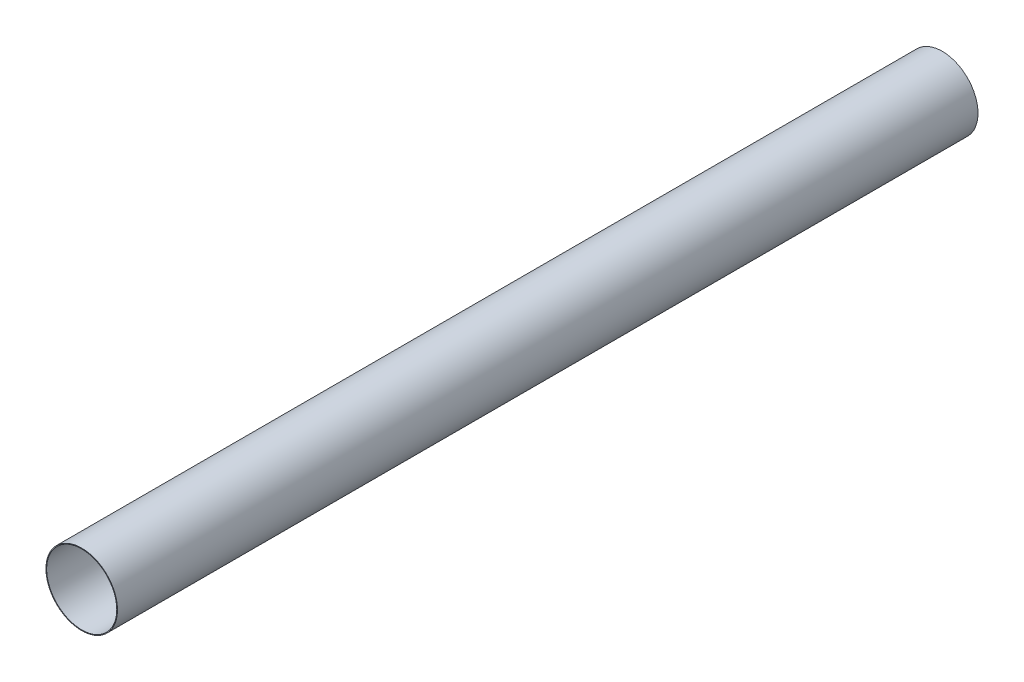
SolidWorks part; units mm, degrees
material "Thornel VCB-20 Carbon Cloth"
ref_plane "Front Plane" through (0, 0, 0) normal (0, 0, 1) x (1, 0, 0)
ref_plane "Top Plane" through (0, 0, 0) normal (0, 1, 0) x (1, 0, 0)
ref_plane "Right Plane" through (0, 0, 0) normal (1, 0, 0) x (0, 0, -1)
sketch "Sketch1" plane through (0, 0, 0) normal (0, 0, 1) x (1, 0, 0)
  circle A0 centre (0, 0) radius 73.5
  circle A1 centre (0, 0) radius 75
  dimension "D1" = 150
  dimension "D2" = 1.5
extrude "Boss-Extrude1" add sketch "Sketch1" along normal blind 1804
